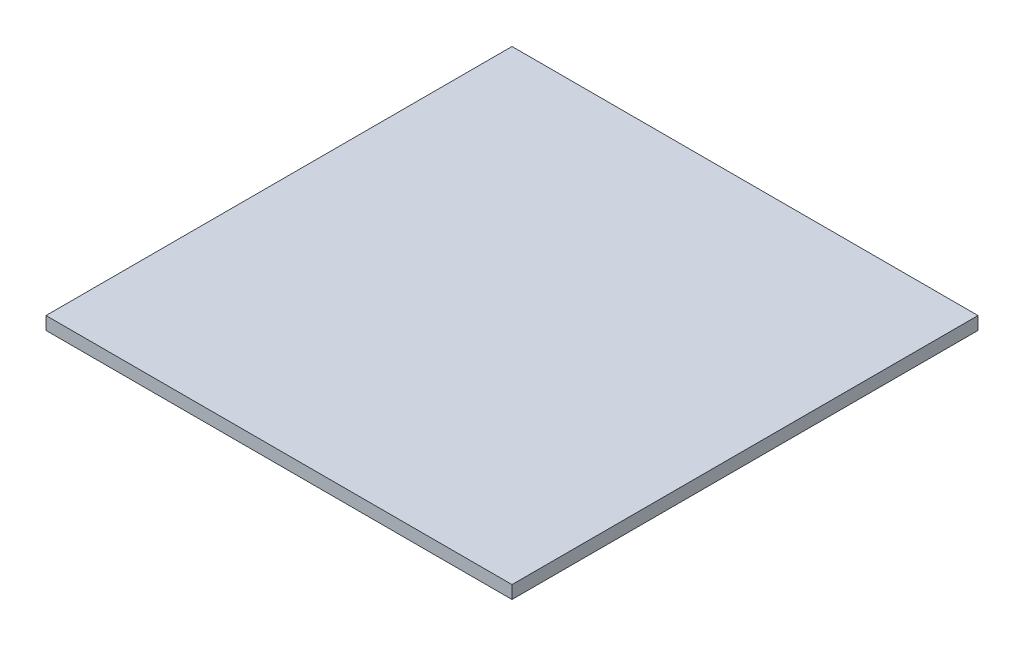
SolidWorks part; units mm, degrees
ref_plane "Front Plane" through (0, 0, 0) normal (0, 0, 1) x (1, 0, 0)
ref_plane "Top Plane" through (0, 0, 0) normal (0, 1, 0) x (1, 0, 0)
ref_plane "Right Plane" through (0, 0, 0) normal (1, 0, 0) x (0, 0, -1)
sketch "Sketch1" plane through (0, 0, 0) normal (0, 1, 0) x (1, 0, 0)
  line L1 (228.6, -228.6) -> (-228.6, -228.6)
  line L2 (228.6, -228.6) -> (228.6, 228.6)
  line L3 (228.6, 228.6) -> (-228.6, 228.6)
  line L4 (-228.6, -228.6) -> (-228.6, 228.6)
  line L5 (228.6, -228.6) -> (-228.6, 228.6) construction
  line L6 (228.6, 228.6) -> (-228.6, -228.6) construction
  point P0 (0, 0)
  dimension "D1" = 457.2
  dimension "D2" = 457.2
extrude "Boss-Extrude1" add sketch "Sketch1" along normal blind 12.7 contours L4 L3 L2 L1
